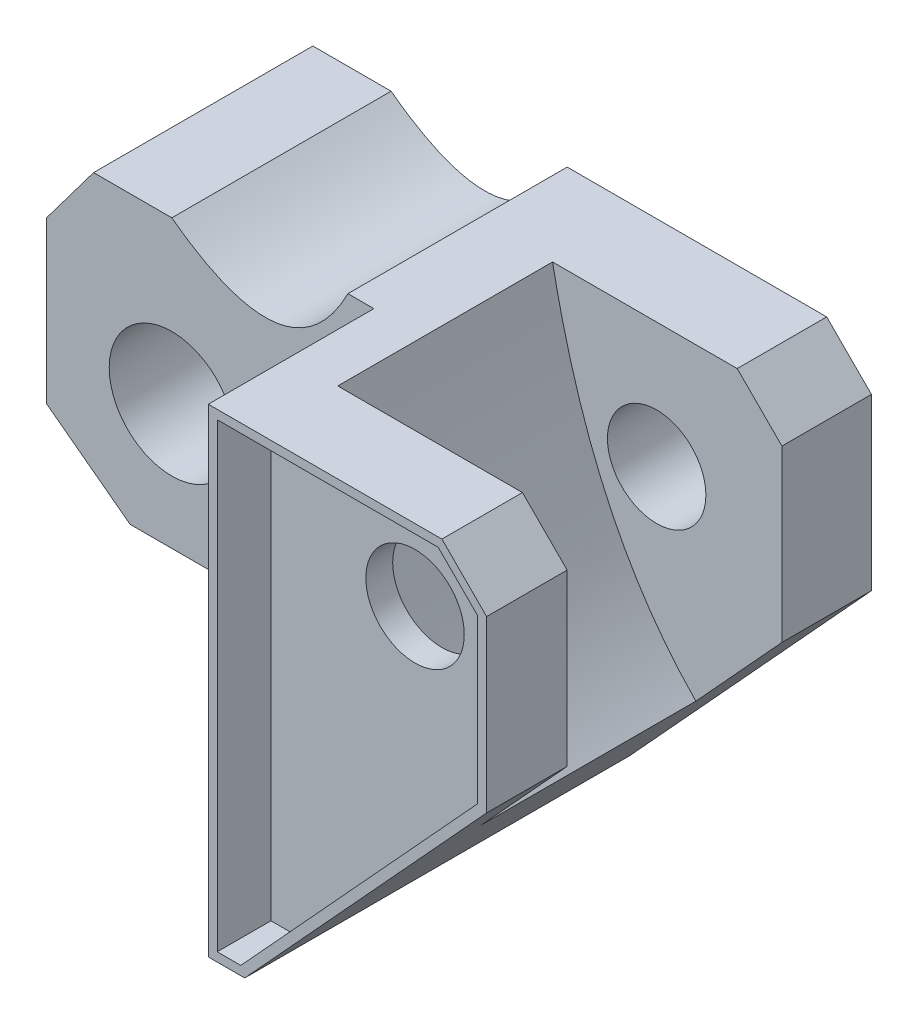
SolidWorks part; units mm, degrees
material "AISI 1020 Steel, Cold Rolled"
ref_plane "Front Plane" through (0, 0, 0) normal (0, 0, 1) x (1, 0, 0)
ref_plane "Top Plane" through (0, 0, 0) normal (0, 1, 0) x (1, 0, 0)
ref_plane "Right Plane" through (0, 0, 0) normal (1, 0, 0) x (0, 0, -1)
sketch "Sketch1" plane through (0, 0, 0) normal (0, 0, 1) x (1, 0, 0)
  line L11 (0, 0) -> (-9.3304, 7)
  line L12 (-9.3304, 7) -> (-9.3304, 25)
  line L13 (-9.3304, 25) -> (-4.0788, 32)
  line L14 (-4.0788, 32) -> (4.6696, 32)
  line L15 (0, 0) -> (18.7066, 0)
  line L16 (18.7066, 0) -> (22.7993, -19)
  line L18 (22.7993, -19) -> (31.3098, -19)
  line L19 (24.3434, 34.495) -> (53.3434, 34.495)
  line L20 (53.3434, 34.495) -> (58.3434, 29.495)
  line L21 (58.3434, 29.495) -> (58.3434, 10.495)
  line L22 (31.3098, -19) -> (58.3434, 10.495)
  spline S0 degree 2 poles (4.6696, 32) (17.9704, 22.0586) (24.3434, 34.495) knots 0 0 0 1 1 1
  dimension "D1" = 7
  dimension "D2" = 7
  dimension "D3" = 14
  dimension "D5" = 29
  dimension "D6" = 5
  dimension "D7" = 135
  dimension "D8" = 24
  dimension "D9" = 67.6738
extrude "Boss-Extrude1" add sketch "Sketch1" along normal blind 43
sketch "Sketch2" plane through (0, 0, 0) normal (0, 0, -1) x (-1, 0, 0)
  line L0 (9.3304, 25) -> (9.3304, 7) construction
  line L2 (0, 0) -> (-18.7066, 0) construction
  circle A0 centre (-4.6696, 14) radius 7
  point P4 (0, 0)
  point P6 (-7.3728, 0)
  dimension "D1" = 14
  dimension "D2" = 14
  dimension "D3" = 14
extrude "Cut-Extrude1" cut sketch "Sketch2" against normal blind 43
sketch "Sketch3" plane through (0, 0, 43) normal (0, 0, 1) x (1, 0, 0)
  line L0 (58.3434, 10.495) -> (58.3434, 29.495) construction
  line L1 (53.3434, 34.495) -> (24.3434, 34.495) construction
  circle A0 centre (44.3434, 20.495) radius 5.5
  dimension "D1" = 11
  dimension "D2" = 14
  dimension "D3" = 14
extrude "Cut-Extrude2" cut sketch "Sketch3" against normal blind 43
sketch "Sketch4" plane through (0, 0, 0) normal (0, 1, 0) x (1, 0, 0)
  line L1 (27.2404, -43.5029) -> (-16.7486, -43.5029)
  line L2 (27.2404, -43.5029) -> (27.2404, -24.5029)
  line L3 (27.2404, -24.5029) -> (-16.7486, -24.5029)
  line L4 (-16.7486, -43.5029) -> (-16.7486, -24.5029)
  dimension "D1" = 19
extrude "Cut-Extrude3" cut sketch "Sketch4" against normal through all both and the other way through all
sketch "Sketch5" plane through (0, 0, 0) normal (0, 1, 0) x (1, 0, 0)
  line L0 (53.3434, 0) -> (24.3434, 0) construction
  line L1 (32.7078, -10) -> (67.78, -10)
  line L2 (32.7078, -10) -> (32.7078, -34)
  line L3 (32.7078, -34) -> (67.78, -34)
  line L4 (67.78, -10) -> (67.78, -34)
  dimension "D1" = 24
  dimension "D2" = 10
extrude "Cut-Extrude4" cut sketch "Sketch5" along normal blind 43 contours L2 L1 L4 L3
sketch "Sketch6" plane through (0, 0, 10) normal (0, 0, 1) x (1, 0, 0)
  line L0 (32.7078, 34.495) -> (32.7078, 0)
  line L1 (32.7078, 0) -> (48.7243, 0)
  spline S0 degree 3 poles (48.7243, 0) (39.5336, 9.3458) (35.1693, 21.9792) (32.7078, 34.495) knots 0 0 0 0 1 1 1 1
extrude "Boss-Extrude2" add sketch "Sketch6" along normal up to surface (24 mm away) up to face at (38.8434, 20.495, 34)
sketch3d "3DSketch1"
  line L0 (30.8699, -18, 43) -> (57.3434, 10.8839, 43)
  line L1 (57.3434, 10.8839, 43) -> (57.3434, 29.0807, 43)
  line L2 (57.3434, 29.0807, 43) -> (52.9292, 33.495, 43)
  line L3 (52.9292, 33.495, 43) -> (28.2404, 33.495, 43)
  line L4 (28.2404, 33.495, 43) -> (28.2404, -18, 43)
  line L5 (28.2404, -18, 43) -> (30.8699, -18, 43)
  line L6 (30.8699, -18, 43) -> (57.3434, 10.8839, 43)
  line L7 (57.3434, 10.8839, 43) -> (57.3434, 29.0807, 43)
  line L8 (57.3434, 29.0807, 43) -> (52.9292, 33.495, 43)
  line L9 (52.9292, 33.495, 43) -> (28.2404, 33.495, 43)
  line L10 (28.2404, 33.495, 43) -> (28.2404, -18, 43)
  line L11 (28.2404, -18, 43) -> (30.8699, -18, 43)
  dimension "D1" = 1
extrude "Cut-Extrude5" cut sketch "3DSketch1" along direction (0, 0, 1) on the side against the normal blind 6
